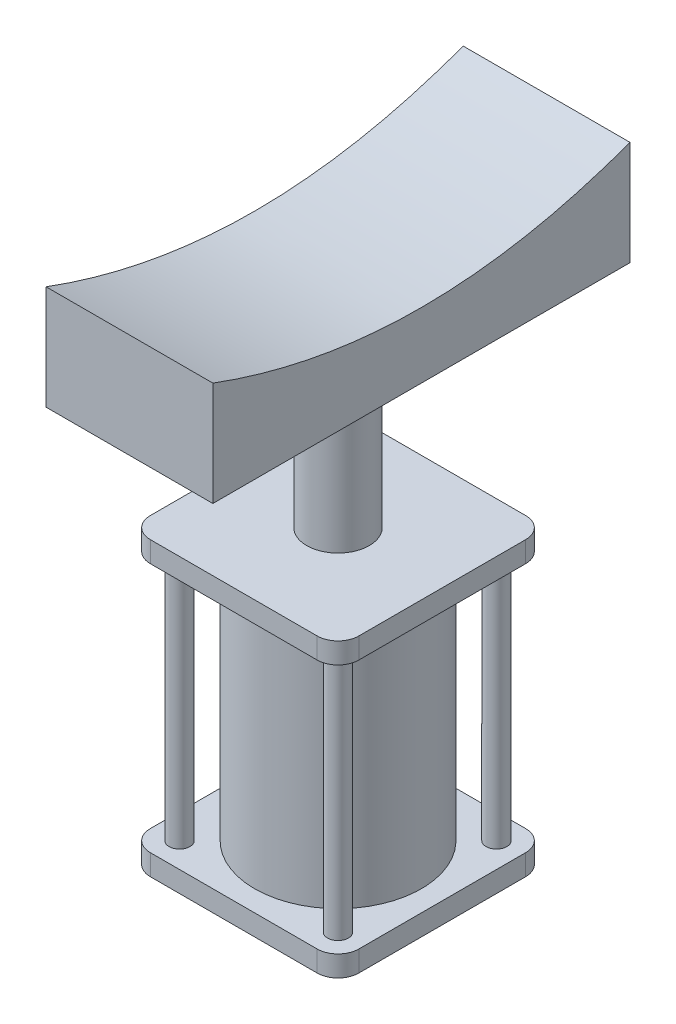
SolidWorks part; units mm, degrees
ref_plane "Front Plane" through (0, 0, 0) normal (0, 0, 1) x (1, 0, 0)
ref_plane "Top Plane" through (0, 0, 0) normal (0, 1, 0) x (1, 0, 0)
ref_plane "Right Plane" through (0, 0, 0) normal (1, 0, 0) x (0, 0, -1)
sketch "Sketch1" plane through (0, 0, 0) normal (0, 1, 0) x (1, 0, 0)
  line L1 (-50, -50) -> (50, -50)
  line L2 (-50, -50) -> (-50, 50)
  line L3 (-50, 50) -> (50, 50)
  line L4 (50, -50) -> (50, 50)
  line L5 (-50, -50) -> (50, 50) construction
  line L6 (-50, 50) -> (50, -50) construction
  point P0 (0, 0)
  dimension "D1" = 100
  dimension "D2" = 100
extrude "Boss-Extrude1" add sketch "Sketch1" along normal blind 10
sketch "Sketch2" plane through (0, 10, 0) normal (0, 1, 0) x (1, 0, 0)
  circle A0 centre (0, 0) radius 40
  dimension "D1" = 80
extrude "Boss-Extrude2" add sketch "Sketch2" along normal blind 120 separate body
sketch "Sketch3" plane through (0, 130, 0) normal (0, 1, 0) x (1, 0, 0)
  line L1 (-50, 50) -> (50, 50)
  line L2 (-50, 50) -> (-50, -50)
  line L3 (-50, -50) -> (50, -50)
  line L4 (50, 50) -> (50, -50)
extrude "Boss-Extrude3" add sketch "Sketch3" along normal blind 10 separate body
sketch "Sketch4" plane through (0, 140, 0) normal (0, 1, 0) x (1, 0, 0)
  circle A0 centre (0, 0) radius 15
  dimension "D1" = 30
extrude "Boss-Extrude4" add sketch "Sketch4" along normal blind 80 separate body
sketch "Sketch5" plane through (0, 10, 0) normal (0, 1, 0) x (1, 0, 0)
  line L0 (-50, 50) -> (-50, -50) construction
  line L1 (50, 50) -> (-50, 50) construction
  line L2 (0, 50) -> (0, 0) construction
  line L3 (0, 0) -> (50, 0) construction
  line L4 (50, -50) -> (50, 50) construction
  circle A0 centre (-38, 38) radius 5
  circle A1 centre (38, 38) radius 5
  circle A2 centre (38, -38) radius 5
  circle A3 centre (-38, -38) radius 5
  dimension "D1" = 10
  dimension "D2" = 12
  dimension "D3" = 12
extrude "Boss-Extrude5" add sketch "Sketch5" along normal up to surface (120 mm away) up to face at (0, 130, 0)
fillet "Fillet1" radius 10 8 edges at (50, 5, -50) (50, 5, 50) (-50, 5, 50) (-50, 5, -50) (-50, 135, -50) (50, 135, -50) (50, 135, 50) (-50, 135, 50)
sketch "Sketch6" plane through (0, 220, 0) normal (0, 1, 0) x (1, 0, 0)
  line L1 (-40, -100) -> (40, -100)
  line L2 (-40, -100) -> (-40, 100)
  line L3 (-40, 100) -> (40, 100)
  line L4 (40, -100) -> (40, 100)
  line L5 (-40, -100) -> (40, 100) construction
  line L6 (-40, 100) -> (40, -100) construction
  point P0 (0, 0)
  dimension "D1" = 200
  dimension "D2" = 80
extrude "Boss-Extrude6" add sketch "Sketch6" along normal blind 50 separate body contours L3 L4 L1 L2
sketch "Sketch7" plane through (40, 0, 0) normal (1, 0, 0) x (0, 0, -1)
  line L0 (-100, 270) -> (100, 270)
  spline S0 degree 2 poles (-100, 270) (0, 232.7889) (100, 270) knots 0 0 0 1 1 1
extrude "Cut-Extrude3" cut sketch "Sketch7" against normal blind 1500 contours S0 L0
